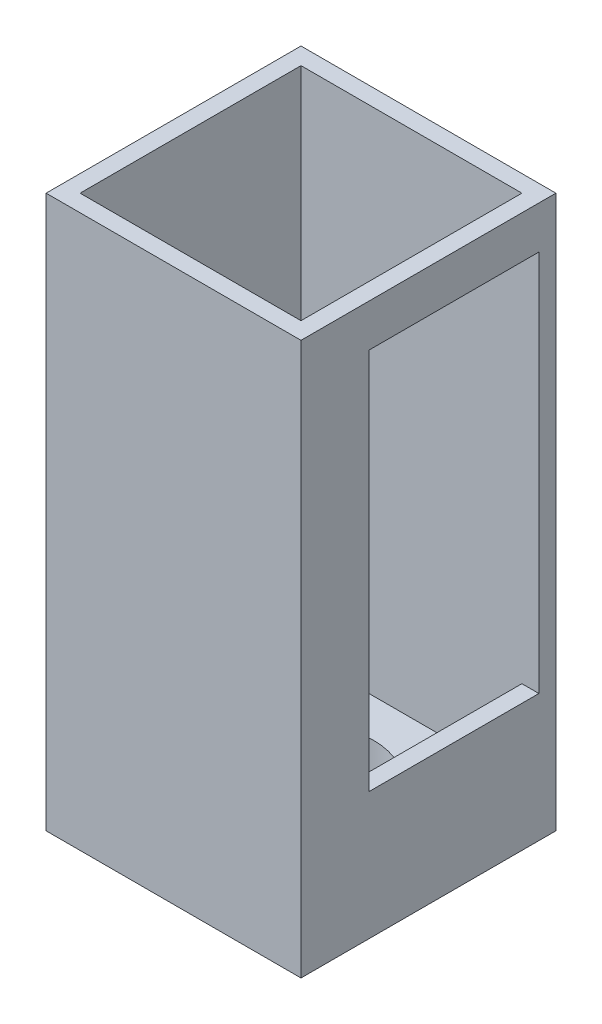
SolidWorks part; units mm, degrees
material "ABS"
ref_plane "Alzado" through (0, 0, 0) normal (0, 0, 1) x (1, 0, 0)
ref_plane "Planta" through (0, 0, 0) normal (0, 1, 0) x (1, 0, 0)
ref_plane "Vista lateral" through (0, 0, 0) normal (1, 0, 0) x (0, 0, -1)
sketch "Croquis1" plane through (0, 0, 0) normal (0, 1, 0) x (1, 0, 0)
  line L1 (-15, -15) -> (15, -15)
  line L2 (-15, -15) -> (-15, 15)
  line L3 (-15, 15) -> (15, 15)
  line L4 (15, -15) -> (15, 15)
  line L5 (-15, -15) -> (15, 15) construction
  line L6 (-15, 15) -> (15, -15) construction
  point P0 (0, 0)
  dimension "D1" = 30
  dimension "D2" = 30
extrude "Saliente-Extruir1" add sketch "Croquis1" along normal blind 60 and the other way blind 5
sketch "Croquis2" plane through (0, 60, 0) normal (0, 1, 0) x (1, 0, 0)
  line L18 (13, -13) -> (13, 13)
  line L19 (-13, -13) -> (13, -13)
  line L20 (-13, 13) -> (-13, -13)
  line L21 (13, 13) -> (-13, 13)
  line L22 (13, -13) -> (13, 13)
  line L23 (-13, -13) -> (13, -13)
  line L24 (-13, 13) -> (-13, -13)
  line L25 (13, 13) -> (-13, 13)
  point P0 (0, 0)
  dimension "D1" = 2
extrude "Cortar-Extruir3" cut sketch "Croquis2" against normal up to surface (65 mm away) up to face at (0, -5, 0)
sketch "Croquis3" plane through (15, 0, 0) normal (1, 0, 0) x (0, 0, -1)
  line L0 (15, -5) -> (15, 60) construction
  line L1 (-7, 10) -> (13, 10)
  line L2 (-7, 10) -> (-7, 55)
  line L3 (-7, 55) -> (13, 55)
  line L4 (13, 10) -> (13, 55)
  line L5 (-15, -5) -> (15, -5) construction
  dimension "D1" = 2
  dimension "D2" = 15
  dimension "D3" = 20
  dimension "D4" = 45
extrude "Cortar-Extruir4" cut sketch "Croquis3" against normal up to surface (2 mm away) up to face at (13, 27.5, 0)
sketch "Croquis4" plane through (0, -5, 0) normal (0, -1, 0) x (1, 0, 0)
  line L1 (-13, 13) -> (13, 13)
  line L2 (-13, 13) -> (-13, -13)
  line L3 (-13, -13) -> (13, -13)
  line L4 (13, 13) -> (13, -13)
extrude "Saliente-Extruir2" add sketch "Croquis4" against normal blind 5
sketch "Croquis5" plane through (0, -5, 0) normal (0, -1, 0) x (1, 0, 0)
  circle A0 centre (0, 0) radius 8.5
  dimension "D1" = 17
extrude "Cortar-Extruir5" cut sketch "Croquis5" against normal up to surface (5 mm away) up to face at (0, 0, 0)
equation "\"9.5.00mm\"=10"
